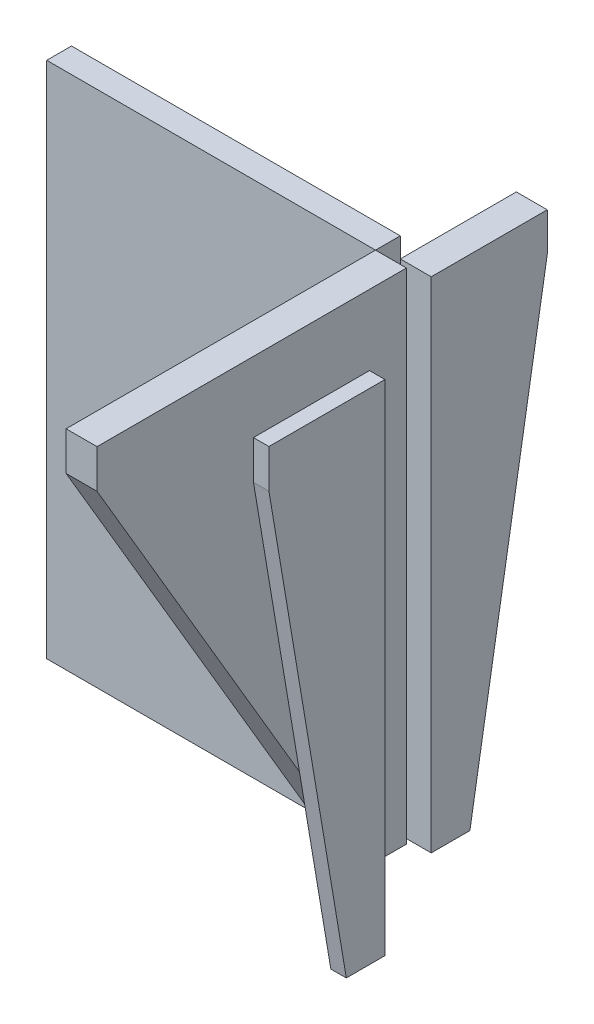
SolidWorks part; units mm, degrees
ref_plane "Front Plane" through (0, 0, 0) normal (0, 0, 1) x (1, 0, 0)
ref_plane "Top Plane" through (0, 0, 0) normal (0, 1, 0) x (1, 0, 0)
ref_plane "Right Plane" through (0, 0, 0) normal (1, 0, 0) x (0, 0, -1)
sketch "Sketch1" plane through (0, 0, 0) normal (0, 0, 1) x (1, 0, 0)
  line L1 (0, 0) -> (425, 0)
  line L2 (0, 0) -> (0, -670)
  line L3 (0, -670) -> (425, -670)
  line L4 (425, 0) -> (425, -670)
  dimension "D1" = 425
  dimension "D2" = 670
extrude "Boss-Extrude1" add sketch "Sketch1" along normal blind 32
sketch "Sketch3" plane through (425, 0, 0) normal (1, 0, 0) x (0, 0, -1)
  line L0 (-32, 0) -> (-432, 0)
  line L1 (-432, 0) -> (-432, -50)
  line L2 (-432, -50) -> (-82, -645)
  line L3 (-82, -645) -> (-32, -645)
  line L4 (-32, -670) -> (-32, 0) construction
  line L5 (-32, -645) -> (-32, 0)
  line L6 (0, -25.8519) -> (150, -25.8519)
  line L7 (0, -670) -> (0, 0) construction
  line L8 (150, -25.8519) -> (150, -75.8519)
  line L9 (150, -75.8519) -> (50, -670.8519)
  line L10 (50, -670.8519) -> (0, -670.8519)
  line L11 (0, -670.8519) -> (0, -25.8519)
  point P15 (10.0163, -670.8519)
  dimension "D1" = 645
  dimension "D2" = 400
  dimension "D3" = 50
  dimension "D4" = 50
  dimension "D5" = 150
  dimension "D6" = 50
  dimension "D7" = 645
  dimension "D8" = 50
extrude "Boss-Extrude2" add sketch "Sketch3" along normal blind 40 separate body
sketch "Sketch4" plane through (465, 0, 0) normal (1, 0, 0) x (0, 0, -1)
  line L0 (-229.7714, -90.9664) -> (-79.7714, -90.9664)
  line L1 (-79.7714, -90.9664) -> (-79.7714, -735.9664)
  line L2 (-79.7714, -735.9664) -> (-129.7714, -735.9664)
  line L3 (-129.7714, -735.9664) -> (-229.7714, -140.9664)
  line L4 (-229.7714, -140.9664) -> (-229.7714, -90.9664)
  dimension "D1" = 50
  dimension "D2" = 50
  dimension "D3" = 150
  dimension "D4" = 645
extrude "Boss-Extrude3" add sketch "Sketch4" along normal blind 20 contours L0 L1 L2 L3 L4
